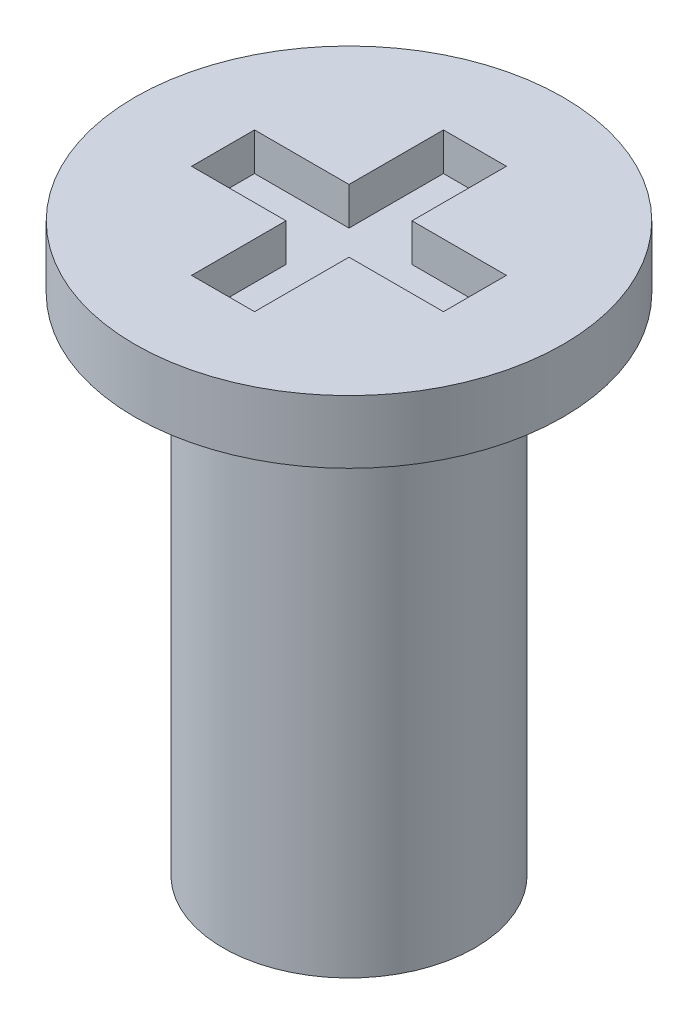
SolidWorks part; units mm, degrees
material "S45C"
ref_plane "正面" through (0, 0, 0) normal (0, 0, 1) x (1, 0, 0)
ref_plane "平面" through (0, 0, 0) normal (0, 1, 0) x (1, 0, 0)
ref_plane "右側面" through (0, 0, 0) normal (1, 0, 0) x (0, 0, -1)
sketch "ｽｹｯﾁ1" plane through (0, 0, 0) normal (0, 0, 1) x (1, 0, 0)
  line L0 (0, 0) -> (1.7, 0)
  line L1 (1.7, 0) -> (1.7, -0.5)
  line L2 (1.7, -0.5) -> (1, -0.5)
  line L3 (1, -0.5) -> (1, -4.5)
  line L4 (1, -4.5) -> (0, -4.5)
  line L5 (0, -4.5) -> (0, 0)
  dimension "D1" = 1.7
  dimension "D2" = 0.5
  dimension "D3" = 1
  dimension "D4" = 4
revolve "回転1" add sketch "ｽｹｯﾁ1" angle 360 about L5
sketch "ｽｹｯﾁ2" plane through (0, 0, 0) normal (0, 1, 0) x (1, 0, 0)
  line L1 (-0.25, 0) -> (0.25, 0)
  line L2 (-0.25, 0) -> (-0.25, 1)
  line L3 (-0.25, 1) -> (0.25, 1)
  line L4 (0.25, 0) -> (0.25, 1)
  line L5 (-0.25, 0) -> (0.25, 1) construction
  line L6 (-0.25, 1) -> (0.25, 0) construction
  point P4 (0, 0.5)
  dimension "D1" = 0
  dimension "D2" = 0.5
  dimension "D3" = 1
  dimension "D4" = 0
extrude "ｶｯﾄ - 押し出し1" cut sketch "ｽｹｯﾁ2" against normal blind 0.3
pattern_circular "円形ﾊﾟﾀｰﾝ1" count 4 over 360 about axis through (0, 0, 0) along (0, 1, 0) of "ｶｯﾄ - 押し出し1"
